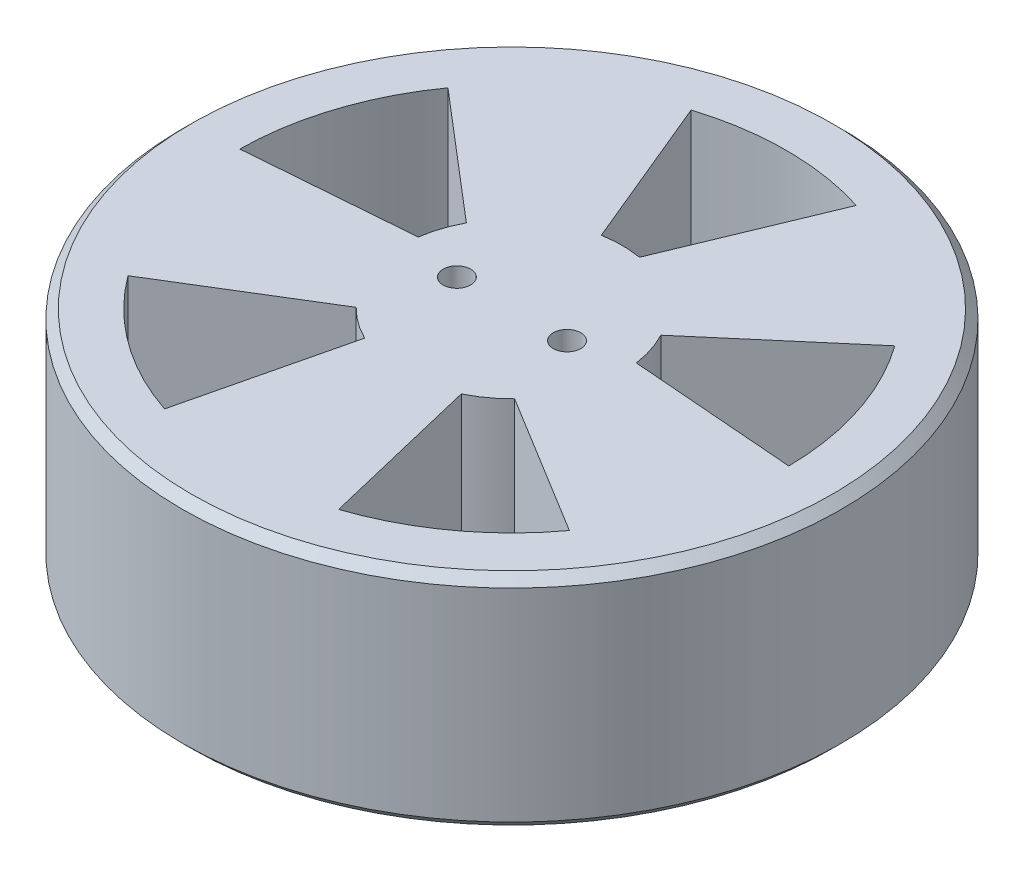
SolidWorks part; units mm, degrees
ref_plane "Front Plane" through (0, 0, 0) normal (0, 0, 1) x (1, 0, 0)
ref_plane "Top Plane" through (0, 0, 0) normal (0, 1, 0) x (1, 0, 0)
ref_plane "Right Plane" through (0, 0, 0) normal (1, 0, 0) x (0, 0, -1)
sketch "Sketch1" plane through (0, 0, 0) normal (0, 1, 0) x (1, 0, 0)
  circle A0 centre (0, 0) radius 76.0095
  dimension "D1" = 152.019
extrude "Boss-Extrude1" add sketch "Sketch1" along normal blind 50.8
chamfer "Chamfer1" distance 2.032 angle 45 2 edges at (0, 0, 76.0095) (0, 50.8, 76.0095)
sketch "Sketch2" plane through (0, 50.8, 0) normal (0, 1, 0) x (1, 0, 0)
  line L0 (-12.7, 0) -> (0, 0) construction
  line L1 (0, 0) -> (12.7, 0) construction
  circle A0 centre (0, 0) radius 25.4 construction
  circle A1 centre (-12.7, 0) radius 3.175
  circle A2 centre (12.7, 0) radius 3.175
  dimension "D1" = 6.35
  dimension "D2" = 50.8
  dimension "D3" = 12.7
  dimension "D4" = 12.7
extrude "Cut-Extrude1" cut sketch "Sketch2" against normal through all both and the other way through all
sketch "Sketch3" plane through (0, 50.8, 0) normal (0, 1, 0) x (1, 0, 0)
  line L0 (0, 25.4) -> (0, 63.3095) construction
  line L1 (-4.4034, 25.0154) -> (-19.05, 60.3754)
  line L2 (4.4034, 25.0154) -> (19.05, 60.3754)
  line L3 (22.4303, 11.9181) -> (51.5337, 36.7747)
  line L4 (25.1518, 3.5423) -> (63.3072, 0.5394)
  line L5 (18.2661, -17.6496) -> (50.8996, -37.6474)
  line L6 (11.1413, -22.8261) -> (20.076, -60.042)
  line L7 (-11.1413, -22.8261) -> (-20.076, -60.042)
  line L8 (-18.2661, -17.6496) -> (-50.8996, -37.6474)
  line L9 (-25.1518, 3.5423) -> (-63.3072, 0.5394)
  line L10 (-22.4303, 11.9181) -> (-51.5337, 36.7747)
  arc A0 (4.4034, 25.0154) -> (-4.4034, 25.0154) centre (0, 0) ccw
  arc A1 (19.05, 60.3754) -> (-19.05, 60.3754) centre (0, 0) ccw
  circle A2 centre (0, 0) radius 76.0095 construction
  arc A3 (-4.4034, 25.0154) -> (4.4034, 25.0154) centre (0, 0) ccw construction
  arc A4 (-19.05, 60.3754) -> (19.05, 60.3754) centre (0, 0) ccw construction
  arc A5 (25.1518, 3.5423) -> (22.4303, 11.9181) centre (0, 0) ccw
  arc A6 (63.3072, 0.5394) -> (51.5337, 36.7747) centre (0, 0) ccw
  arc A7 (11.1413, -22.8261) -> (18.2661, -17.6496) centre (0, 0) ccw
  arc A8 (20.076, -60.042) -> (50.8996, -37.6474) centre (0, 0) ccw
  arc A9 (-18.2661, -17.6496) -> (-11.1413, -22.8261) centre (0, 0) ccw
  arc A10 (-50.8996, -37.6474) -> (-20.076, -60.042) centre (0, 0) ccw
  arc A11 (-22.4303, 11.9181) -> (-25.1518, 3.5423) centre (0, 0) ccw
  arc A12 (-51.5337, 36.7747) -> (-63.3072, 0.5394) centre (0, 0) ccw
  point P28 (0, 0)
  dimension "D1" = 12.7
  dimension "D2" = 50.8
  dimension "D3" = 45
  dimension "D4" = 22.5
  dimension "D5" = 19.05
  dimension "D6" = 19.05
  dimension "D7" = 5
extrude "Cut-Extrude2" cut sketch "Sketch3" against normal through all both and the other way through all
equation "\"OD\"= 6"
equation "\"offset\" = 0.015"
equation "\"L\" = 2"
equation "\"D1@Sketch1\"=\"OD\"-\"offset\""
equation "\"D1@Boss-Extrude1\"=\"L\""
